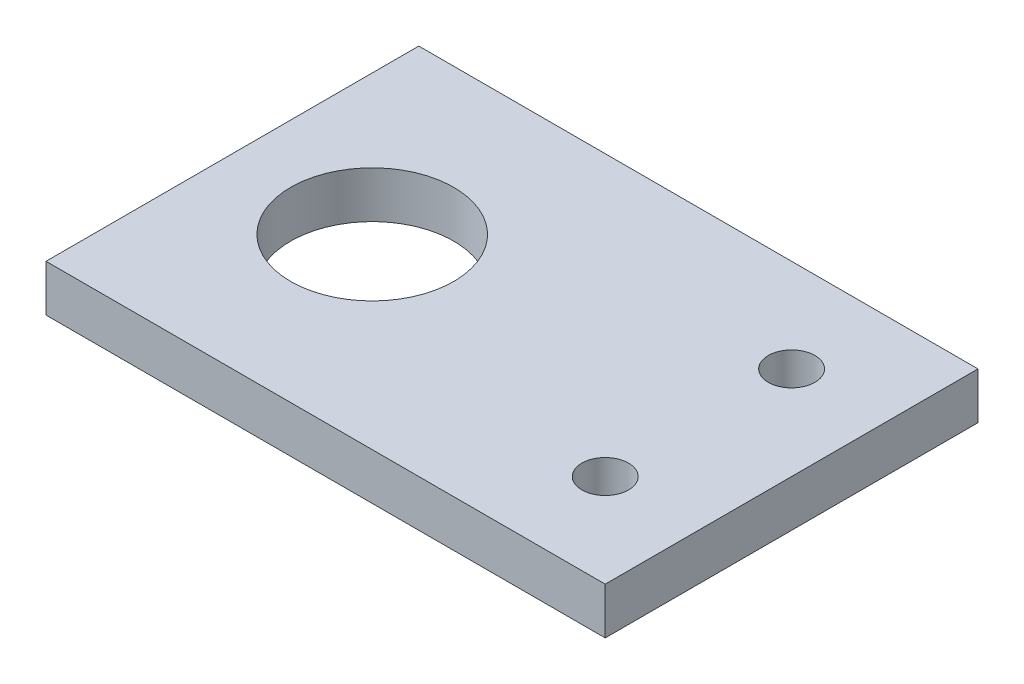
SolidWorks part; units mm, degrees
ref_plane "Front Plane" through (0, 0, 0) normal (0, 0, 1) x (1, 0, 0)
ref_plane "Top Plane" through (0, 0, 0) normal (0, 1, 0) x (1, 0, 0)
ref_plane "Right Plane" through (0, 0, 0) normal (1, 0, 0) x (0, 0, -1)
sketch "Sketch1" plane through (0, 0, 0) normal (0, 1, 0) x (1, 0, 0)
  line L1 (-178.9683, 59.1511) -> (-102.7683, 59.1511)
  line L2 (-178.9683, 59.1511) -> (-178.9683, 8.3511)
  line L3 (-178.9683, 8.3511) -> (-102.7683, 8.3511)
  line L4 (-102.7683, 59.1511) -> (-102.7683, 8.3511)
  line L5 (-178.9683, 59.1511) -> (-102.7683, 8.3511) construction
  line L6 (-178.9683, 8.3511) -> (-102.7683, 59.1511) construction
  point P0 (-140.8683, 33.7511)
  dimension "D1" = 76.2
  dimension "D2" = 50.8
extrude "Boss-Extrude1" add sketch "Sketch1" along normal blind 6.35
sketch "Sketch2" plane through (0, 6.35, 0) normal (0, 1, 0) x (1, 0, 0)
  line L0 (-178.9683, 33.7511) -> (-102.7683, 33.7511) construction
  line L1 (-178.9683, 59.1511) -> (-178.9683, 8.3511) construction
  line L2 (-102.7683, 8.3511) -> (-102.7683, 59.1511) construction
  line L3 (-115.4683, 59.1511) -> (-115.4683, 8.3511) construction
  line L4 (-102.7683, 59.1511) -> (-178.9683, 59.1511) construction
  line L5 (-178.9683, 8.3511) -> (-102.7683, 8.3511) construction
  circle A0 centre (-159.9183, 33.7511) radius 11.1125
  circle A1 centre (-115.4683, 46.4511) radius 3.175
  circle A2 centre (-115.4683, 21.0511) radius 3.175
  dimension "D1" = 57.15
  dimension "D3" = 12.7
  dimension "D4" = 12.7
  dimension "D2" = 12.7
extrude "Cut-Extrude1" cut sketch "Sketch2" against normal through all
